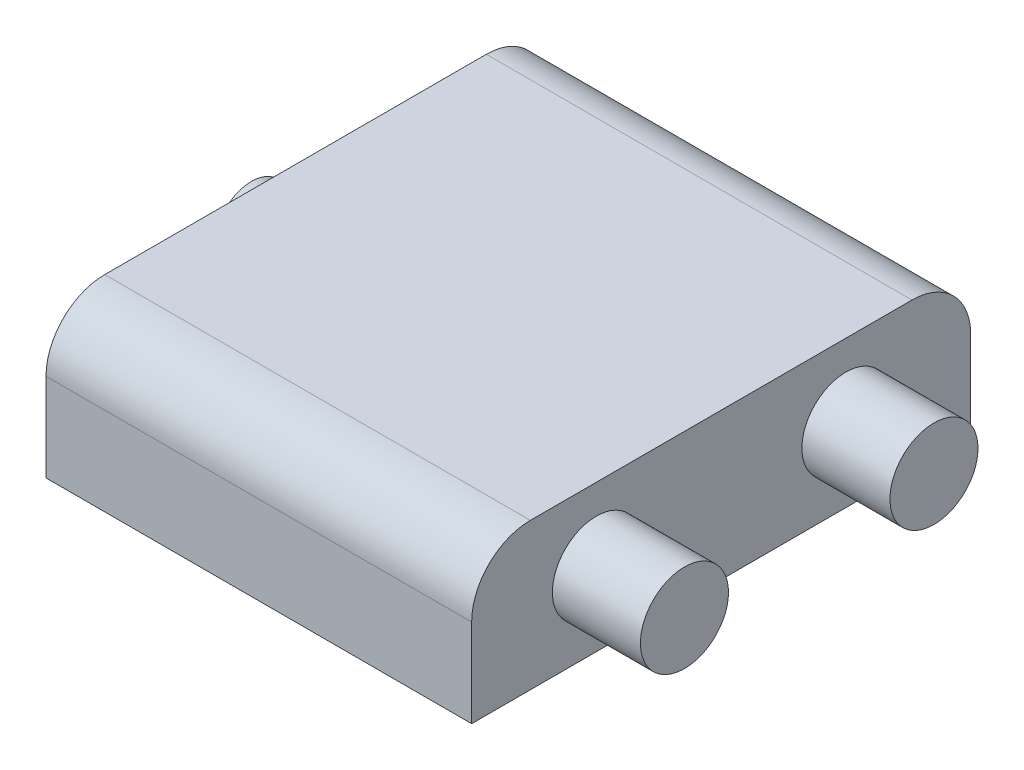
SolidWorks part; units mm, degrees
ref_plane "Plano frontal" through (0, 0, 0) normal (0, 0, 1) x (1, 0, 0)
ref_plane "Plano superior" through (0, 0, 0) normal (0, 1, 0) x (1, 0, 0)
ref_plane "Plano direito" through (0, 0, 0) normal (1, 0, 0) x (0, 0, -1)
sketch "Esboço1" plane through (0, 0, 0) normal (1, 0, 0) x (0, 0, -1)
  line L1 (17, -5) -> (-17, -5)
  line L2 (17, -5) -> (17, 5)
  line L3 (17, 5) -> (-17, 5)
  line L4 (-17, -5) -> (-17, 5)
  line L5 (17, -5) -> (-17, 5) construction
  line L6 (17, 5) -> (-17, -5) construction
  point P0 (0, 0)
  dimension "D1" = 10
  dimension "D2" = 34
extrude "Ressalto-extrusão1" add sketch "Esboço1" along normal blind 29
fillet "Filete1" radius 4 2 edges at (14.5, 5, 17) (14.5, 5, -17)
sketch "Esboço2" plane through (29, 0, 0) normal (1, 0, 0) x (0, 0, -1)
  line L2 (0, 0) -> (-8.5, 0)
  line L3 (0, 0) -> (0, -3.1413)
  circle A0 centre (-8.5, 0) radius 3
  circle A1 centre (8.5, 0) radius 3
  dimension "D2" = 6
  dimension "D1" = 8.5
extrude "Ressalto-extrusão2" add sketch "Esboço2" along normal blind 6
sketch "Esboço3" plane through (0, 0, 0) normal (-1, 0, 0) x (0, 0, 1)
  circle A0 centre (0, 0) radius 2.5
  dimension "D1" = 5
extrude "Ressalto-extrusão3" add sketch "Esboço3" along normal blind 3
